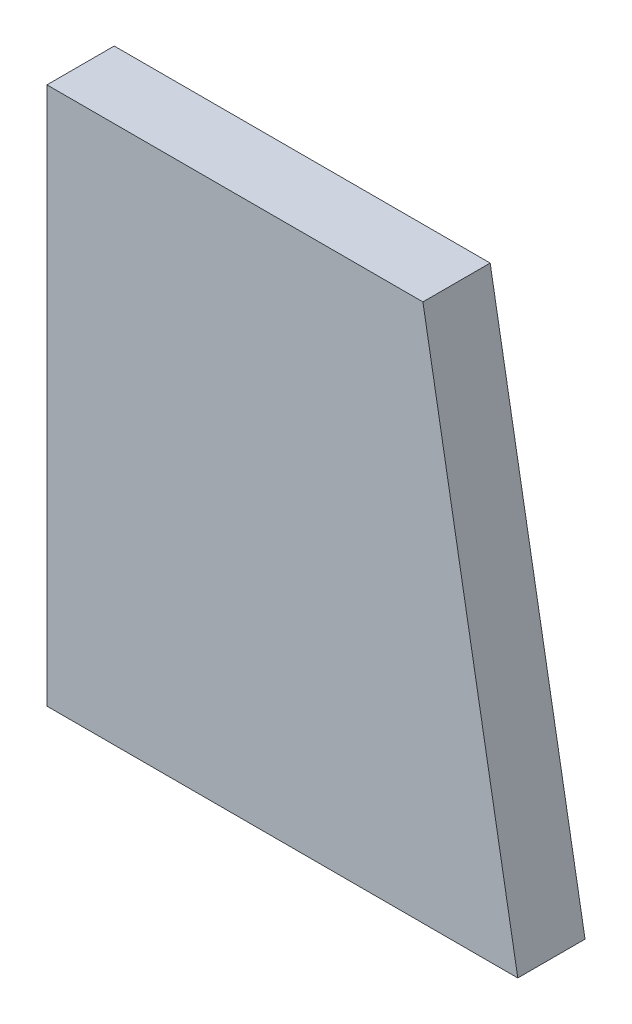
SolidWorks part; units mm, degrees
ref_plane "Plan de face" through (0, 0, 0) normal (0, 0, 1) x (1, 0, 0)
ref_plane "Plan de dessus" through (0, 0, 0) normal (0, 1, 0) x (1, 0, 0)
ref_plane "Plan de droite" through (0, 0, 0) normal (1, 0, 0) x (0, 0, -1)
sketch "Esquisse1" plane through (0, 0, 0) normal (0, 0, 1) x (1, 0, 0)
  line L0 (0, 0) -> (-35, 0)
  line L1 (-35, 0) -> (-35, 40)
  line L2 (-35, 40) -> (-7.0531, 40)
  line L3 (-7.0531, 40) -> (0, 0)
  dimension "D1" = 35
  dimension "D2" = 40
  dimension "D3" = 80
extrude "Boss.-Extru.1" add sketch "Esquisse1" along normal blind 5
